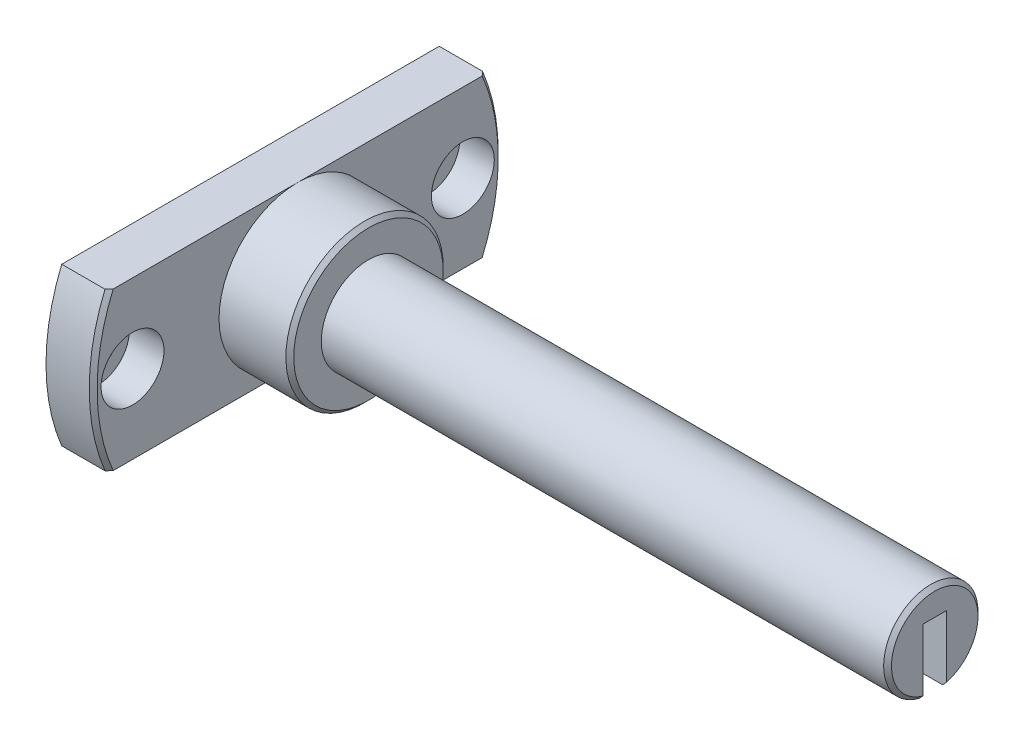
SolidWorks part; units mm, degrees
material "3.1325 (EN-AW 2017A)"
ref_plane "Plan de face" through (0, 0, 0) normal (0, 0, 1) x (1, 0, 0)
ref_plane "Plan de dessus" through (0, 0, 0) normal (0, 1, 0) x (1, 0, 0)
ref_plane "Plan de droite" through (0, 0, 0) normal (1, 0, 0) x (0, 0, -1)
sketch "Esquisse1" plane through (0, 0, 0) normal (0, 0, 1) x (1, 0, 0)
  line L0 (15, 6) -> (87, 6)
  line L1 (87, 6) -> (87, 0)
  line L2 (87, 0) -> (0, 0)
  line L3 (0, 0) -> (0, 26)
  line L4 (6, 10) -> (15, 10)
  line L5 (15, 10) -> (15, 6)
  line L7 (0, 26) -> (6, 26)
  line L8 (6, 26) -> (6, 10)
  dimension "D1" = 87
  dimension "D3" = 6
  dimension "D4" = 15
  dimension "D5" = 6
  dimension "D6" = 10
  dimension "D7" = 20
revolve "Révolution1" add sketch "Esquisse1" angle 360 about L2
chamfer "Chanfrein1" distance 0.5 angle 45 2 edges at (15, 10, 0) (6, 26, 0)
hole_wizard "Chambrage pour vis à tête hexagonale M41" positions "Esquisse4" profile "Esquisse2" counterbore size "M4" standard "ISO" end condition through all
sketch "Esquisse4" plane through (6, 0, 0) normal (1, 0, 0) x (0, 0, -1)
  line L0 (21, 0) -> (0, 0) construction
  line L1 (0, 0) -> (-21, 0) construction
  line L2 (0, 5.6863) -> (0, -6.4906) construction
  point P0 (-21, 0)
  point P2 (21, 0)
  dimension "D1" = 42
sketch "Esquisse2" plane through (6, 0, 21) normal (0, 1, 0) x (0, 0, -1)
  line L0 (0, 0) -> (0, 6)
  line L1 (0, 6) -> (2.25, 6)
  line L3 (2.25, 6) -> (2.25, 4.4)
  line L4 (2.25, 4.4) -> (4, 4.4)
  line L5 (4, 4.4) -> (4, 0)
  line L7 (4, 0) -> (0, 0)
  line L11 (0, -6.35) -> (0, 107.95) construction
  dimension "Diamètre du perçage jusqu'au prochain" = 4.5
  dimension "Profondeur du perçage jusqu'au prochain" = 6
  dimension "Diamètre du chambrage" = 8
  dimension "Profondeur du chambrage" = 4.4
sketch "Esquisse9" plane through (6, 0, 0) normal (1, 0, 0) x (0, 0, -1)
  point P0 (-21, 0)
  point P1 (21, 0)
sketch "Esquisse10" plane through (87, 0, 0) normal (1, 0, 0) x (0, 0, -1)
  line L0 (0, 15.042) -> (0, -18.3339) construction
sketch "Esquisse11" plane through (0, 0, 0) normal (-1, 0, 0) x (0, 0, 1)
  line L0 (24, -10) -> (-24, -10)
  line L2 (-33.9621, 0) -> (34.1744, 0) construction
  line L3 (24, 10) -> (-24, 10)
  circle A0 centre (0, 0) radius 26 construction
  arc A1 (-24, -10) -> (24, -10) centre (0, 0) ccw
  arc A2 (-24, 10) -> (24, 10) centre (0, 0) cw
  dimension "D1" = 20
extrude "Enlèv. mat.-Extru.2" cut sketch "Esquisse11" against normal through all
chamfer "Chanfrein3" distance 0.5 angle 45 1 edges at (87, 6, 0)
sketch "Esquisse12" plane through (87, 0, 0) normal (1, 0, 0) x (0, 0, -1)
  line L1 (-1.5, -9.0025) -> (1.5, -9.0025)
  line L2 (-1.5, -9.0025) -> (-1.5, 2.6186)
  line L3 (-1.5, 2.6186) -> (1.5, 2.6186)
  line L4 (1.5, -9.0025) -> (1.5, 2.6186)
  line L5 (-1.5, -9.0025) -> (1.5, 2.6186) construction
  line L6 (-1.5, 2.6186) -> (1.5, -9.0025) construction
  point P0 (0, 0)
  dimension "D1" = 3
extrude "Enlèv. mat.-Extru.3" cut sketch "Esquisse12" against normal blind 3
hole_wizard "Dégagement M21" positions "Esquisse14" profile "Esquisse15" hole size "M2" standard "JIS"
sketch "Esquisse14" plane through (84, 0, 0) normal (1, 0, 0) x (0, 0, -1)
  point P1 (0, 0)
  point P4 (0, -3.7249)
sketch "Esquisse15" plane through (84, 0, 0) normal (0, 1, 0) x (0, 0, -1)
  line L0 (0, 0) -> (0, 5.6928)
  line L1 (0, 5.6928) -> (1.2, 5)
  line L2 (1.2, 5) -> (1.2, 0)
  line L5 (1.2, 0) -> (0, 0)
  line L10 (0, 5.6928) -> (-1.2, 5) construction
  line L11 (0, -6.35) -> (0, 107.95) construction
  dimension "Diamètre du perçage" = 2.4
  dimension "Profondeur du perçage" = 5
  dimension "Angle de pointe" = 120
